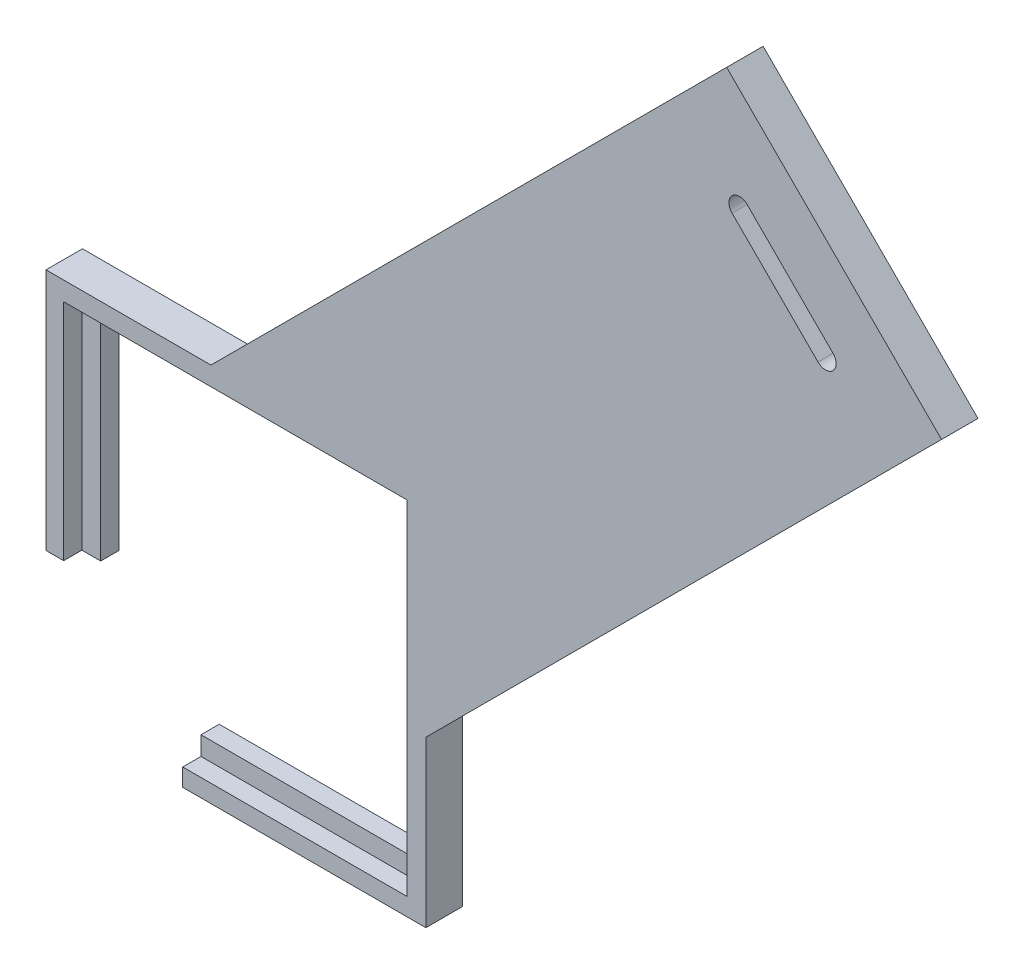
SolidWorks part; units mm, degrees
ref_plane "前视基准面" through (0, 0, 0) normal (0, 0, 1) x (1, 0, 0)
ref_plane "上视基准面" through (0, 0, 0) normal (0, 1, 0) x (1, 0, 0)
ref_plane "右视基准面" through (0, 0, 0) normal (1, 0, 0) x (0, 0, -1)
sketch "草图1" plane through (0, 0, 0) normal (0, 0, 1) x (1, 0, 0)
  line L0 (0, 0) -> (147.7798, 147.7798) construction
  line L1 (22.5, 0) -> (62.5, 0)
  line L2 (0, 22.5) -> (0, 62.5)
  line L3 (0, 62.5) -> (27.1447, 62.5)
  line L4 (62.5, 0) -> (62.5, 27.1447)
  line L6 (56.5, 56.5) -> (6, 56.5)
  line L7 (56.5, 56.5) -> (56.5, 6)
  line L8 (56.5, 6) -> (22.5, 6)
  line L9 (6, 56.5) -> (6, 22.5)
  line L10 (0, 22.5) -> (6, 22.5)
  line L11 (22.5, 6) -> (22.5, 0)
  line L12 (27.1447, 62.5) -> (111.9975, 147.3528)
  line L13 (111.9975, 147.3528) -> (147.3528, 111.9975)
  line L14 (147.3528, 111.9975) -> (62.5, 27.1447)
  dimension "D3" = 34
  dimension "D4" = 22.5
  dimension "D5" = 22.5
  dimension "D6" = 50.5
  dimension "D7" = 6
  dimension "D9" = 120
  dimension "D10" = 50
  dimension "D11" = 45
  dimension "D12" = 45
  dimension "D13" = 25
  dimension "D14" = 25
extrude "凸台-拉伸1" add sketch "草图1" along normal blind 6
sketch "草图2" plane through (0, 0, 6) normal (0, 0, 1) x (1, 0, 0)
  line L0 (0, 0) -> (2.9065, 2.9065) construction
  line L1 (59.4065, 59.4065) -> (2.9065, 59.4065)
  line L2 (59.4065, 59.4065) -> (59.4065, 2.9065)
  line L3 (59.4065, 2.9065) -> (2.9065, 2.9065)
  line L4 (2.9065, 59.4065) -> (2.9065, 2.9065)
  line L5 (22.5, 0) -> (62.5, 0) construction
  dimension "D1" = 56.5
  dimension "D2" = 45
extrude "切除-拉伸1" cut sketch "草图2" against normal blind 3
sketch "草图3" plane through (0, 0, 6) normal (0, 0, 1) x (1, 0, 0)
  line L0 (114.1188, 128.2609) -> (128.2609, 114.1188) construction
  line L3 (147.3528, 111.9975) -> (111.9975, 147.3528) construction
  line L4 (111.9975, 147.3528) -> (27.1447, 62.5) construction
  line L5 (112.8814, 127.0235) -> (127.0235, 112.8814)
  line L6 (115.3562, 129.4984) -> (129.4984, 115.3562)
  arc A0 (112.8814, 127.0235) -> (115.3562, 129.4984) centre (114.1188, 128.2609) cw
  arc A1 (127.0235, 112.8814) -> (129.4984, 115.3562) centre (128.2609, 114.1188) ccw
  point P6 (129.6751, 129.6751)
  dimension "D1" = 20
  dimension "D2" = 15
  dimension "D3" = 12
  dimension "D4" = 1.75
  dimension "D5" = 1.75
extrude "切除-拉伸2" cut sketch "草图3" against normal blind 6
